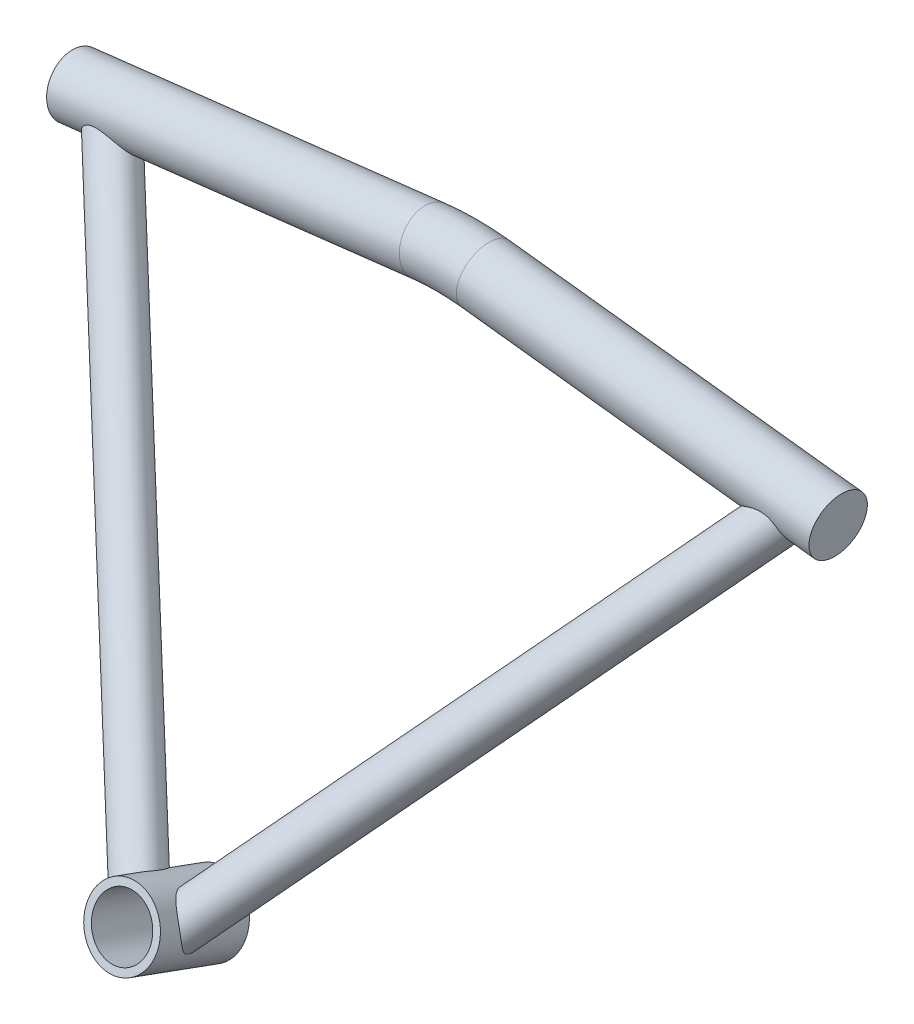
SolidWorks part; units mm, degrees
material "AISI 4130 Steel, normalized at 870C"
ref_plane "Front Plane" through (0, 0, 0) normal (0, 0, 1) x (1, 0, 0)
ref_plane "Top Plane" through (0, 0, 0) normal (0, 1, 0) x (1, 0, 0)
ref_plane "Right Plane" through (0, 0, 0) normal (1, 0, 0) x (0, 0, -1)
sketch "Sketch3" plane through (0, 0, 0) normal (0, 1, 0) x (1, 0, 0)
  line L0 (-5.08, -6.35) -> (5.08, -6.35) construction
  line L2 (0, -88.2205) -> (0, 88.2205) construction
  line L3 (5.08, 0) -> (-5.08, 0) construction
  dimension "D1" = 5.08
  dimension "D2" = 10.16
  dimension "D3" = 6.35
  dimension "D4" = 10.16
  dimension "D5" = 5.08
ref_plane "Plane1" through (0, 3.0807, 3.9431) normal (0, 0.6157, 0.788) x (1, 0, 0)
ref_plane "Plane3" through (0, 0, 0) normal (0, 0.342, 0.9397) x (-1, 0, 0)
sketch "Sketch1" plane through (0, 0, 0) normal (0, 0.342, 0.9397) x (1, 0, 0)
  circle A0 centre (0, 0) radius 15.875
  dimension "D1" = 31.75
extrude "Boss-Extrude1" add sketch "Sketch1" along normal mid plane 41.402 contours A0
sketch "Sketch4" plane through (0, 3.0807, 3.9431) normal (0, 0.6157, 0.788) x (1, 0, 0)
  line L0 (-5.08, -3.9095) -> (-147.115, 206.6661)
  line L2 (0, -89.5666) -> (0, 89.5666) construction
  dimension "D2" = 34
  dimension "D3" = 254
sweep "Sweep1" add path "Sketch4" circular profile diameter 19.05 parameters "D3"=19.05
sketch "Sketch15" plane through (0, 3.0807, 3.9431) normal (0, 0.6157, 0.788) x (1, 0, 0)
  line L0 (5.08, -3.9095) -> (147.115, 206.6661)
  line L1 (0, -89.5666) -> (0, 89.5666) construction
  dimension "D1" = 254
  dimension "D2" = 34
sweep "Sweep2" add path "Sketch15" circular profile diameter 19.05 parameters "D3"=19.05
sketch "Sketch36" plane through (-141.8111, 165.6742, -129.4389) normal (-0.5592, 0.6533, -0.5104) x (0.8289, 0.4282, -0.36)
  circle A0 centre (-6.4965, -4.8749) radius 7.9375
  dimension "D1" = 15.875
extrude "Cut-Extrude2" cut sketch "Sketch36" against normal up to surface (263.9627 mm away)
sketch "Sketch37" plane through (141.8111, 165.6742, -129.4389) normal (0.5592, 0.6533, -0.5104) x (0.8289, -0.4282, 0.36)
  circle A0 centre (6.4965, -4.8749) radius 7.9375
  dimension "D1" = 15.875
extrude "Cut-Extrude3" cut sketch "Sketch37" against normal up to surface (239.4455 mm away)
sketch "Sketch77" plane through (0, 7.0802, 19.4526) normal (0, 0.342, 0.9397) x (1, 0, 0)
  circle A1 centre (0, 0) radius 15.875
extrude "Boss-Extrude2" add sketch "Sketch77" against normal up to surface (41.402 mm away) up to face at (0, -21.9978, -14.023)
sketch "Sketch2" plane through (0, -7.0802, -19.4526) normal (0, -0.342, -0.9397) x (-1, 0, 0)
  circle A0 centre (0, 0) radius 12.7
  dimension "D1" = 25.4
extrude "Cut-Extrude1" cut sketch "Sketch2" against normal up to next
ref_plane "Plane2" through (0, 0, -127) normal (0, 0, 1) x (1, 0, 0)
sketch "Sketch40" plane through (-106.934, 0, -127) normal (0, 0, 1) x (1, 0, 0)
  line L2 (106.934, -90.5202) -> (106.934, 90.5202) construction
  line L3 (94.4829, 187.4611) -> (-59.7307, 169.3775)
  line L4 (119.3851, 187.4611) -> (273.5987, 169.3775)
  arc A0 (94.4829, 187.4611) -> (119.3851, 187.4611) centre (106.934, 81.28) cw
  point P0 (106.934, 188.1886)
  point P7 (106.934, 188.1886)
  dimension "D1" = 155.2702
  dimension "D3" = 106.9086
  dimension "D2" = 155.2702
  dimension "D4" = 7.6
  dimension "D5" = 106.9086
sweep "Sweep3" add path "Sketch40" circular profile diameter 25.4 parameters "D3"=25.4
